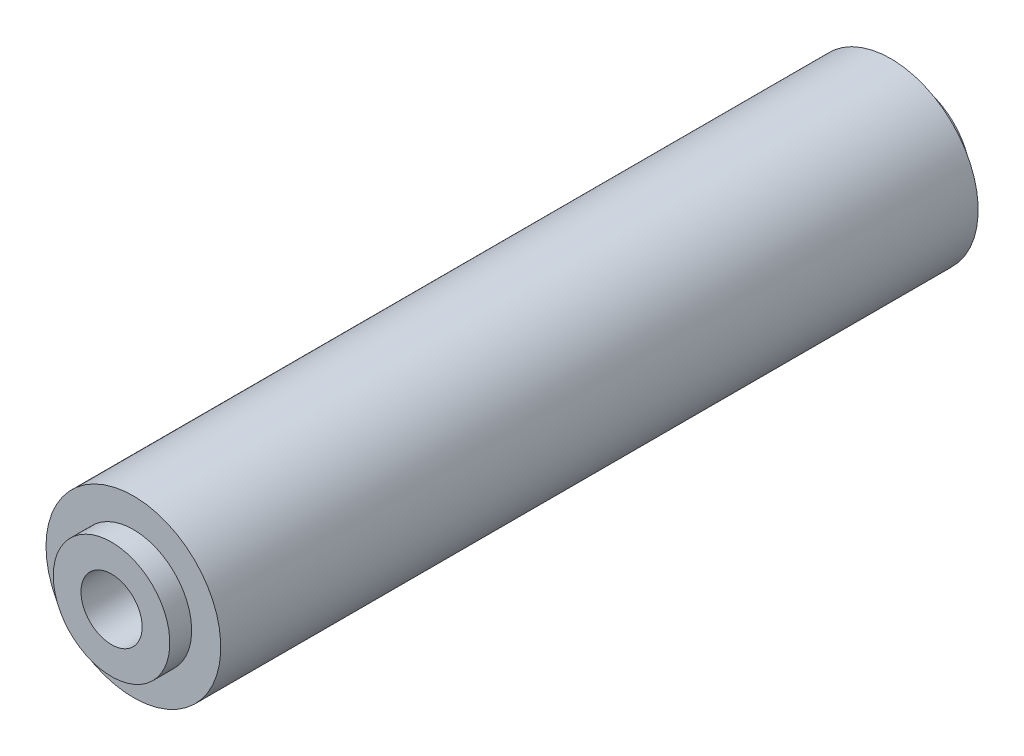
SolidWorks part; units mm, degrees
material "Ti-5Al-2.5Sn 退火 (SS)"
ref_plane "前视基准面" through (0, 0, 0) normal (0, 0, 1) x (1, 0, 0)
ref_plane "上视基准面" through (0, 0, 0) normal (0, 1, 0) x (1, 0, 0)
ref_plane "右视基准面" through (0, 0, 0) normal (1, 0, 0) x (0, 0, -1)
sketch "草图2" plane through (0, 0, 0) normal (1, 0, 0) x (0, 0, -1)
  line L0 (0, 0) -> (0, 90) construction
  line L1 (0, 90) -> (27.5, 90) construction
  line L2 (27.5, 86) -> (27.5, 94) construction
  line L3 (27.5, 94) -> (26, 94)
  line L4 (26, 94) -> (26, 96)
  line L5 (26, 96) -> (-26, 96)
  line L6 (-27.5, 86) -> (-27.5, 94) construction
  line L7 (-27.5, 94) -> (-26, 94)
  line L8 (-26, 94) -> (-26, 96)
  line L9 (-27.5, 86) -> (-26, 86) construction
  line L10 (-26, 86) -> (-26, 84) construction
  line L11 (26, 84) -> (-26, 84) construction
  line L12 (26, 86) -> (26, 84) construction
  line L13 (27.5, 86) -> (26, 86) construction
  line L14 (0, 90) -> (-27.5, 90) construction
  line L15 (-27.5, 90) -> (-27.5, 94)
  line L16 (27.5, 94) -> (27.5, 90)
  line L17 (27.5, 90) -> (-27.5, 90)
  point P12 (0, 96)
  point P13 (-27.5, 90)
  point P18 (0, 84)
  dimension "D1" = 55
  dimension "D2" = 52
  dimension "D3" = 12
  dimension "D4" = 8
  dimension "D5" = 90
revolve "旋转4" add sketch "草图2" angle 360 about L17
hole_wizard "M5x0.8 螺纹孔的螺纹孔钻头1" positions "草图3" profile "草图5" hole size "M5x0.8" standard "ANSI Metric"
sketch "草图3" plane through (0, 0, 27.5) normal (0, 0, 1) x (1, 0, 0)
  point P0 (0, 90)
  point P3 (-58.0682, 20.8726)
sketch "草图5" plane through (0, 90, 27.5) normal (1, 0, 0) x (0, -1, 0)
  line L0 (0, 0) -> (0, 16.2618)
  line L1 (0, 16.2618) -> (2.1, 15)
  line L2 (2.1, 15) -> (2.1, 0)
  line L5 (2.1, 0) -> (0, 0)
  line L10 (0, 16.2618) -> (-2.1, 15) construction
  line L11 (0, -6.35) -> (0, 107.95) construction
  dimension "孔直径" = 4.2
  dimension "孔深度" = 15
  dimension "导头角度" = 118
mirror "镜向1" about plane through (0, 0, 0) normal (0, 0, 1) of "M5x0.8 螺纹孔的螺纹孔钻头1"
